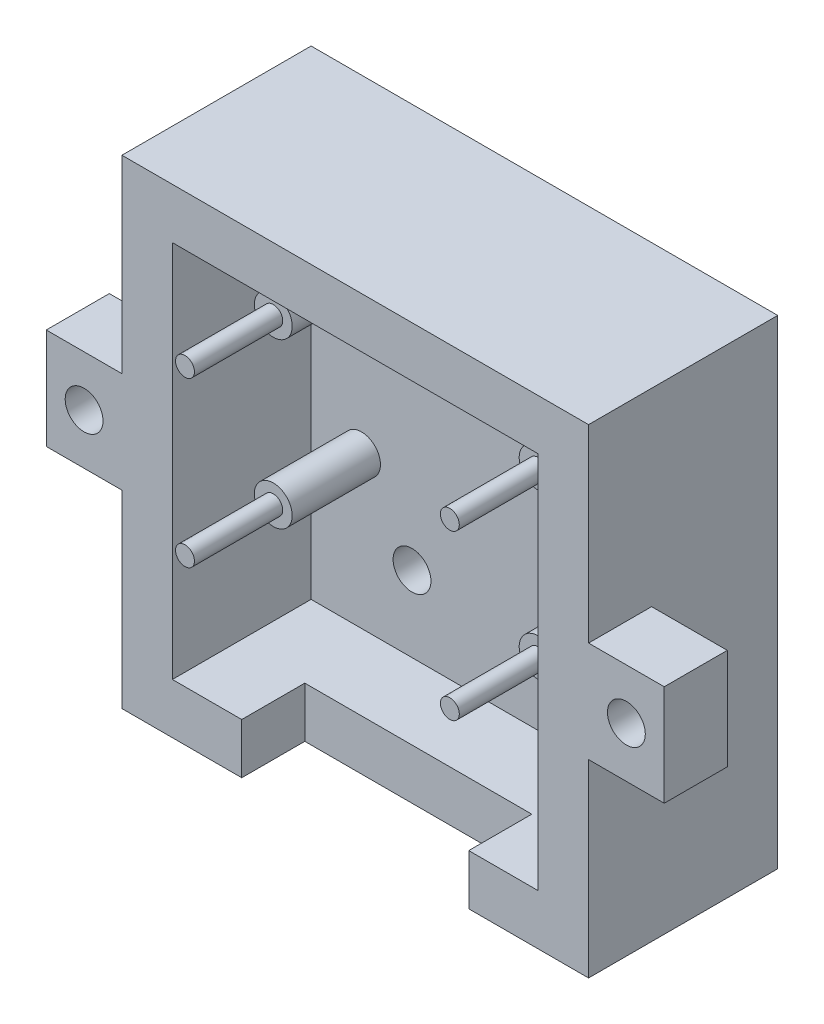
SolidWorks part; units mm, degrees
ref_plane "Alzado" through (0, 0, 0) normal (0, 0, 1) x (1, 0, 0)
ref_plane "Planta" through (0, 0, 0) normal (0, 1, 0) x (1, 0, 0)
ref_plane "Vista lateral" through (0, 0, 0) normal (1, 0, 0) x (0, 0, -1)
sketch "Croquis1" plane through (0, 0, 0) normal (0, 0, 1) x (1, 0, 0)
  line L1 (-18.5, 19) -> (18.5, 19)
  line L2 (-18.5, 19) -> (-18.5, -19)
  line L3 (-18.5, -19) -> (18.5, -19)
  line L4 (18.5, 19) -> (18.5, -19)
  point P4 (0, 19)
  point P5 (-18.5, 0)
  point P9 (0, 0)
  dimension "D1" = 37
  dimension "D2" = 38
extrude "Saliente-Extruir1" add sketch "Croquis1" along normal blind 15
shell "Vaciado1" thickness 4
sketch "Croquis2" plane through (0, 0, 15) normal (0, 0, 1) x (1, 0, 0)
  line L0 (18.5, 4) -> (24.5, 4)
  line L1 (18.5, -19) -> (18.5, 19) construction
  line L2 (24.5, 4) -> (24.5, -4)
  line L3 (24.5, -4) -> (18.5, -4)
  circle A0 centre (21.5, 0) radius 1.5
  point P4 (24.5, 0)
  point P10 (0, 0)
  point P11 (21.5, 4)
  line M10 (18.5, -19) -> (18.5, 19)
  dimension "D3" = 3
  dimension "D1" = 8
  dimension "D2" = 6
  dimension "D4" = 4
extrude "Saliente-Extruir2" add sketch "Croquis2" against normal blind 5 contours L3 L2 L0 A0 M10
mirror "Simetría1" about plane through (0, 0, 0) normal (1, 0, 0) of "Saliente-Extruir2"
sketch "Croquis3" plane through (0, -19, 0) normal (0, -1, 0) x (1, 0, 0)
  line L0 (-18.5, 15) -> (18.5, 15) construction
  line L1 (-9, 15) -> (9, 15)
  line L2 (-9, 15) -> (-9, 10)
  line L3 (-9, 10) -> (9, 10)
  line L4 (9, 15) -> (9, 10)
  point P6 (0, 10)
  dimension "D1" = 18
  dimension "D2" = 5
extrude "Cortar-Extruir1" cut sketch "Croquis3" against normal blind 5
sketch "Croquis4" plane through (0, 0, 4) normal (0, 0, 1) x (1, 0, 0)
  line L5 (-14.5, 15) -> (-14.5, -15)
  line L6 (-14.5, -15) -> (14.5, -15)
  line L7 (14.5, -15) -> (14.5, 15)
  line L8 (14.5, 15) -> (-14.5, 15)
  line L10 (-14.5, -15) -> (14.5, -15)
  line L11 (14.5, -15) -> (14.5, 15)
  line L12 (14.5, 15) -> (-14.5, 15)
  circle A0 centre (10.5, -3) radius 1.5
  circle A1 centre (10.5, 10) radius 1.5
  circle A2 centre (-10.5, 10) radius 1.5
  circle A3 centre (-10.5, -3) radius 1.5
  point P8 (0, 0)
  point P9 (0, 0)
  point P10 (0, 0)
  point P11 (0, 0)
  dimension "D3" = 3
  dimension "D1" = 13
  dimension "D2" = 21
  dimension "D5" = 5
  dimension "D6" = 4
  dimension "D4" = 0
extrude "Saliente-Extruir3" add sketch "Croquis4" along normal blind 7 contours A2 | A1 | A0 | A3
sketch "Croquis5" plane through (0, 0, 11) normal (0, 0, 1) x (1, 0, 0)
  circle A0 centre (-10.5, 10) radius 0.75
  circle A1 centre (10.5, 10) radius 0.75
  circle A9 centre (10.5, -3) radius 0.75
  circle A10 centre (-10.5, -3) radius 0.75
  dimension "D1" = 1.5
extrude "Saliente-Extruir4" add sketch "Croquis5" along normal blind 7
sketch "Croquis7" plane through (0, 0, 4) normal (0, 0, 1) x (1, 0, 0)
  circle A0 centre (-6.5, 9) radius 1.5
  circle A1 centre (6.5, 9) radius 1.5
  circle A2 centre (6.5, -9) radius 1.5
  circle A3 centre (-6.5, -9) radius 1.5
  point P8 (0, 0)
  point P9 (0, 0)
  point P10 (0, 0)
  point P11 (0, 0)
  dimension "D1" = 3
  dimension "D2" = 13
  dimension "D3" = 18
  dimension "D4" = 9
  dimension "D5" = 6.5
extrude "Cortar-Extruir2" cut sketch "Croquis7" against normal blind 7
equation "\"D6@Croquis4\"=(29-21)/2"
equation "\"D4@Croquis7\"=\"D3@Croquis7\"/2"
equation "\"D5@Croquis7\"=\"D2@Croquis7\"/2"
